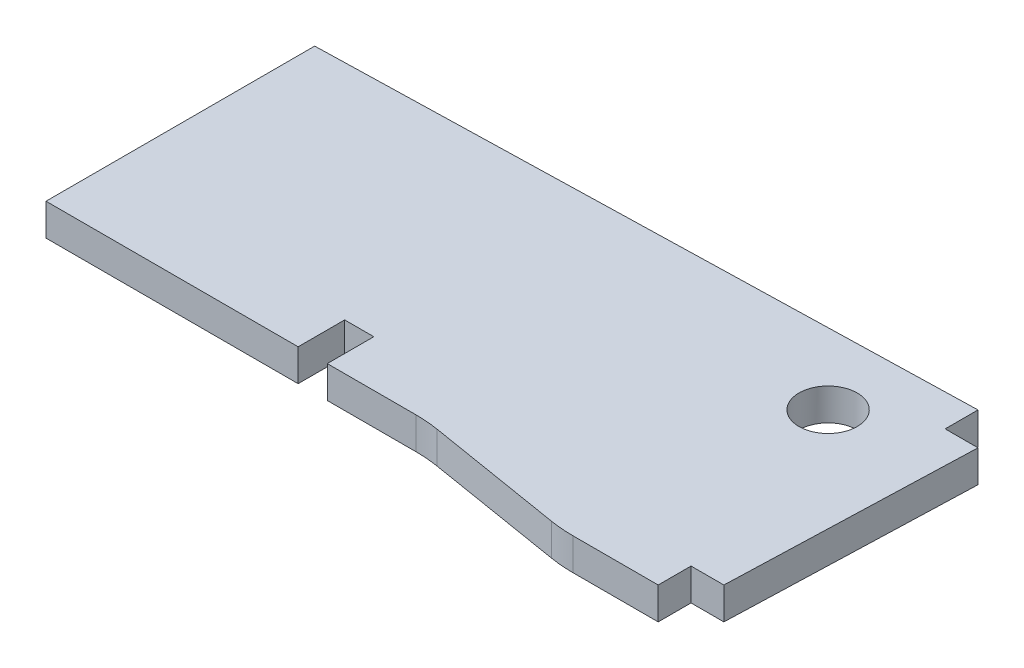
SolidWorks part; units mm, degrees
material "Motor Mount Side"
ref_plane "Front Plane" through (0, 0, 0) normal (0, 0, 1) x (1, 0, 0)
ref_plane "Top Plane" through (0, 0, 0) normal (0, 1, 0) x (1, 0, 0)
ref_plane "Right Plane" through (0, 0, 0) normal (1, 0, 0) x (0, 0, -1)
sketch "Sketch1" plane through (0, 0, 0) normal (0, 1, 0) x (1, 0, 0)
  line L0 (0, 0) -> (0, 23.9014)
  line L1 (0, 23.9014) -> (57.531, 25.3746)
  line L2 (57.531, 25.3746) -> (57.531, 22.4536)
  line L3 (57.531, 22.4536) -> (60.452, 22.4536)
  line L4 (60.452, 22.4536) -> (59.7154, 0.5842)
  line L5 (59.7154, 0.5842) -> (56.7944, 0.5842)
  line L6 (56.7944, 0.5842) -> (56.7944, -2.3368)
  line L7 (0, 0) -> (33.9344, 0)
  line L8 (56.7944, -2.3368) -> (48.1584, -2.3368)
  line L9 (33.9344, 0) -> (48.1584, -2.3368)
  dimension "D1" = 60.452
  dimension "D2" = 2.921
  dimension "D3" = 22.86
  dimension "D4" = 59.7154
  dimension "D5" = 8.636
  dimension "D6" = 23.9014
  dimension "D7" = 21.8694
  dimension "D9" = 1.4732
extrude "Boss-Extrude1" add sketch "Sketch1" along normal blind 2.8448
fillet "Fillet1" radius 12.7 2 edges at (48.1584, 1.4224, 2.3368) (33.9344, 1.4224, 0)
sketch "Sketch2" plane through (0, 2.8448, 0) normal (0, 1, 0) x (1, 0, 0)
  line L0 (0, 0) -> (32.8981, 0) construction
  line L1 (22.4282, 0) -> (25.019, 0)
  line L2 (22.4282, 0) -> (22.4282, 4.1402)
  line L3 (22.4282, 4.1402) -> (25.019, 4.1402)
  line L4 (25.019, 0) -> (25.019, 4.1402)
  line L5 (0, 23.9014) -> (0, 0) construction
  dimension "D1" = 4.1402
  dimension "D2" = 2.5908
  dimension "D3" = 22.4282
extrude "Cut-Extrude1" cut sketch "Sketch2" against normal up to next
sketch "Sketch3" plane through (0, 2.8448, 0) normal (0, 1, 0) x (1, 0, 0)
  line L0 (48.26, 18.7198) -> (48.26, 31.4977) construction
  line L1 (0, 23.9014) -> (0, 0) construction
  line L2 (50.8508, 16.129) -> (40.3347, 16.129) construction
  line L3 (49.1947, -2.3368) -> (56.7944, -2.3368) construction
  circle A0 centre (50.8508, 18.7198) radius 2.5908
  dimension "D1" = 5.1816
  dimension "D2" = 48.26
  dimension "D3" = 18.4658
extrude "Cut-Extrude2" cut sketch "Sketch3" against normal up to next
